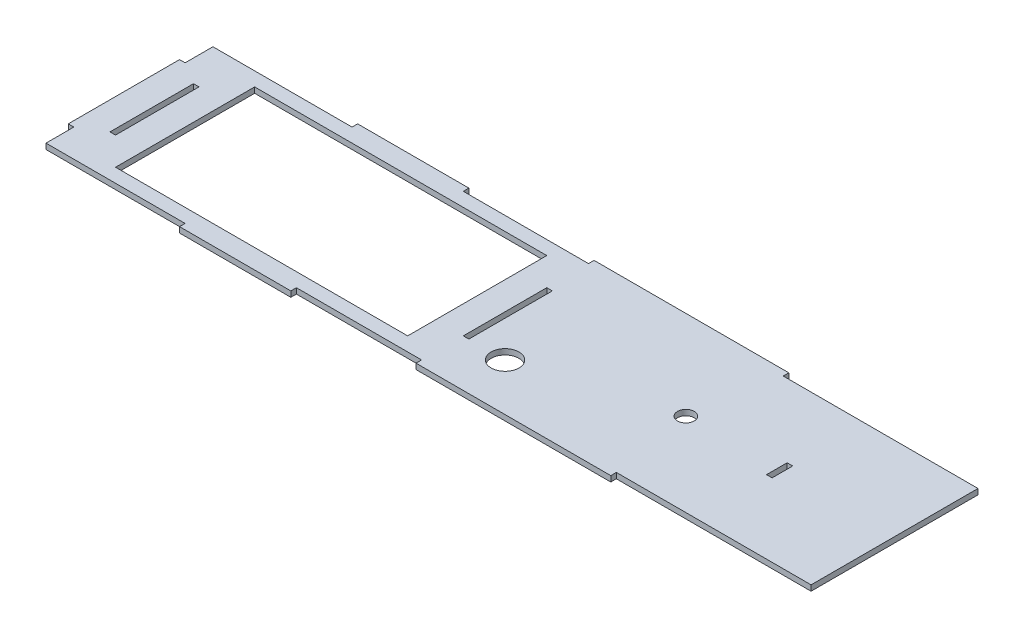
SolidWorks part; units mm, degrees
ref_plane "前视基准面" through (0, 0, 0) normal (0, 0, 1) x (1, 0, 0)
ref_plane "上视基准面" through (0, 0, 0) normal (0, 1, 0) x (1, 0, 0)
ref_plane "右视基准面" through (0, 0, 0) normal (1, 0, 0) x (0, 0, -1)
sketch "草图1" plane through (0, 0, 0) normal (0, 1, 0) x (1, 0, 0)
  line L0 (-2, -30) -> (-2, 30)
  line L1 (-2, -30) -> (275, -30)
  line L2 (-2, 30) -> (275, 30)
  line L3 (275, -30) -> (275, 30)
  line L4 (135, 15) -> (137, 15)
  line L5 (135, 15) -> (135, -15)
  line L6 (137, 15) -> (137, -15)
  line L7 (135, -15) -> (137, -15)
  line L8 (8, 15) -> (10, 15)
  line L9 (8, 15) -> (8, -15)
  line L10 (10, 15) -> (10, -15)
  line L11 (8, -15) -> (10, -15)
  line L16 (-2, 30) -> (-2, 20)
  line L17 (-2, 30) -> (0, 30)
  line L18 (-2, 20) -> (0, 20)
  line L19 (0, 30) -> (0, 20)
  line L20 (-2, -20) -> (-2, -30)
  line L21 (-2, -20) -> (0, -20)
  line L22 (-2, -30) -> (0, -30)
  line L23 (0, -20) -> (0, -30)
  line L24 (20, 25) -> (20, -25)
  line L25 (20, 25) -> (125, 25)
  line L26 (20, -25) -> (125, -25)
  line L27 (125, 25) -> (125, -25)
  line L28 (232.7, 3.7) -> (232.7, -3.7)
  line L29 (232.7, 3.7) -> (234.7, 3.7)
  line L30 (232.7, -3.7) -> (234.7, -3.7)
  line L31 (234.7, 3.7) -> (234.7, -3.7)
  line L32 (50, 32) -> (50, 30)
  line L33 (50, 32) -> (90, 32)
  line L34 (50, 30) -> (90, 30)
  line L35 (90, 32) -> (90, 30)
  line L36 (50, -30) -> (50, -32)
  line L37 (50, -30) -> (90, -30)
  line L38 (50, -32) -> (90, -32)
  line L39 (90, -30) -> (90, -32)
  line L40 (135, 32) -> (135, 30)
  line L41 (135, 32) -> (205, 32)
  line L42 (135, 30) -> (205, 30)
  line L43 (205, 32) -> (205, 30)
  line L44 (135, -30) -> (135, -32)
  line L45 (135, -30) -> (205, -30)
  line L46 (135, -32) -> (205, -32)
  line L47 (205, -30) -> (205, -32)
  circle A0 centre (200, 0) radius 3
  circle A1 centre (150, -15) radius 5
  point P0 (0, 30)
  point P3 (0, -30)
  point P4 (0, 20)
  point P5 (0, -20)
  point P6 (-2, -20)
  point P7 (-2, 20)
  point P8 (135, -15)
  point P11 (137, 15)
  point P12 (135, 15)
  point P13 (133, -15)
  point P14 (8, 15)
  point P15 (10, 15)
  point P16 (8, -15)
  point P17 (10, -15)
  point P26 (200, 1)
  point P27 (0, 0)
  point P30 (0, 0)
  point P33 (200, -1)
  point P34 (232.7, 3.7)
  point P35 (0, 0)
  point P36 (0, 0)
  point P41 (182.7, 0)
  point P42 (232.7, -3.7)
  point P43 (0, 0)
  point P44 (0, 0)
  point P47 (217, 1.5)
  point P48 (217, -1.5)
  point P51 (50, 30)
  point P56 (50, 32)
  point P57 (50, -30)
  point P58 (50, -32)
  point P59 (90, 30)
  point P60 (90, 32)
  point P61 (90, -30)
  point P64 (90, -32)
  point P65 (135, 32)
  point P66 (135, 30)
  point P67 (135, -30)
  point P68 (135, -32)
  point P69 (205, 32)
  point P70 (205, -30)
  point P71 (205, 30)
  point P72 (205, -32)
  point P73 (0, 0)
  point P84 (0, 0)
  point P85 (0, 0)
  point P86 (0, 0)
  point P89 (0, 0)
extrude "凸台-拉伸1" add sketch "草图1" along normal blind 2
